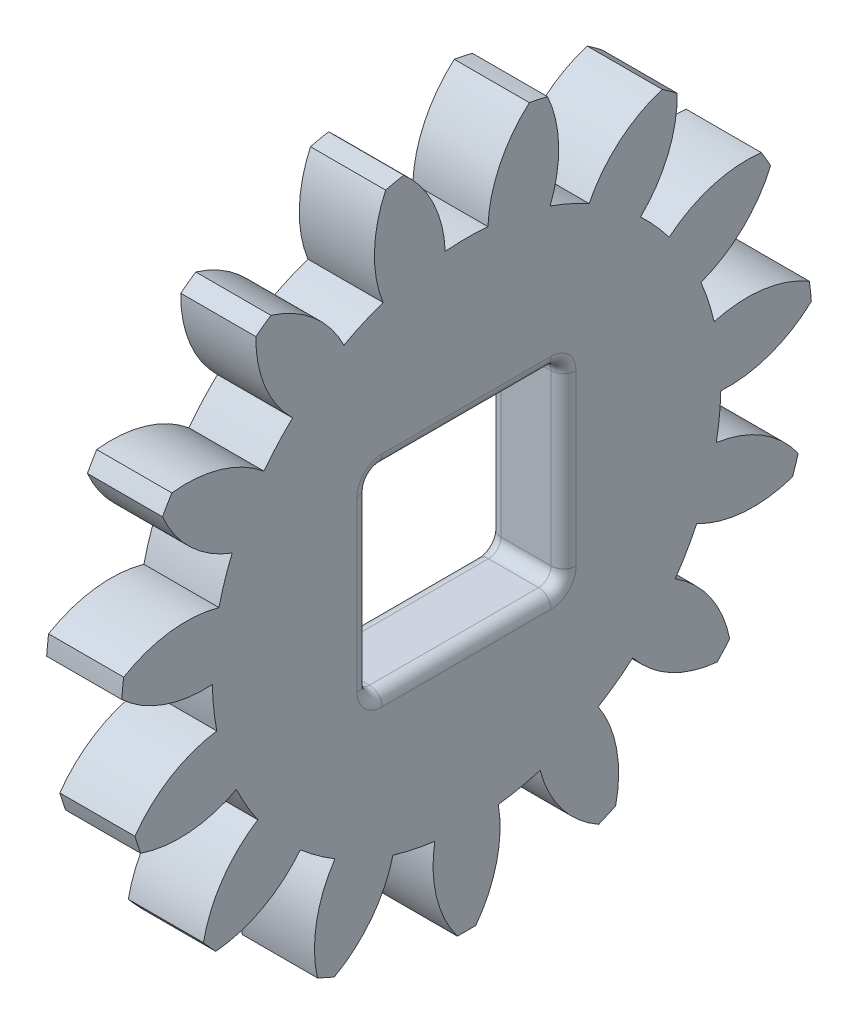
SolidWorks part; units mm, degrees
ref_plane "Plane1" through (0, 0, 0) normal (0, 0, 1) x (1, 0, 0)
ref_plane "Plane2" through (0, 0, 0) normal (0, 1, 0) x (1, 0, 0)
ref_plane "Plane3" through (0, 0, 0) normal (1, 0, 0) x (0, 0, -1)
sketch "HoldingSke" plane through (0, 0, 0) normal (0, 1, 0) x (1, 0, 0)
  line L0 (0, 0) -> (0.1486, -0.0398)
  line L1 (-15, 0) -> (100, 0) construction
  line L2 (0, 0) -> (-2.1039, 2.3779)
  line L3 (0, 0) -> (-11.863, 4.5341)
  line L4 (0, 0) -> (8.3417, 2.2352)
  line L5 (0, 0) -> (-46.8476, -17.4728)
  line L6 (0, 0) -> (-9.9476, -6.7116)
  line L7 (-2.1039, 2.3779) -> (8.6586, 51.2059)
  line L8 (-76.2, 54.61) -> (-73.4, 54.61)
  line L9 (-71.009, 38.7566) -> (-53.1078, 45.2721)
  line L10 (-76.2, 71.12) -> (104.1128, 71.12)
  line L11 (0, 0) -> (-12, 0)
  line L12 (-76.2, 101.6) -> (-75.981, 101.6)
  line L13 (24.9733, 27.94) -> (52.9518, 28.4284)
  line L14 (24.9733, 27.94) -> (24.9743, 27.94)
  line L15 (24.9733, 27.94) -> (100.4006, 29.5858)
  line L16 (-63.627, -6.5) -> (-12.827, -6.5)
  circle A0 centre (0, 0) radius 10
  circle A1 centre (0, 0) radius 37.5
  circle A2 centre (0, 0) radius 37.5
  circle A3 centre (0, 0) radius 10
  dimension "MHD" = 75
  dimension "Hub_dia" = 75
  dimension "Bore" = 20
  dimension "MBD" = 20
  dimension "Num_teeth" = 15
  dimension "Pitch" = 0.1538
  dimension "Overall_len" = 50
  dimension "Show_teeth" = 15
  dimension "Thickness" = 12
  dimension "OAL" = 50.0001
  dimension "T_dim" = 2.8
  dimension "Ap" = 20
  dimension "H" = 19.05
  dimension "Pitch_radius" = 180.3128
  dimension "Width" = 12
  dimension "Backlash" = 0.219
  dimension "Addendum_fac" = 1
  dimension "Dedendum_fac" = 1.25
  dimension "Clearance_fac" = 0.25
  dimension "Dedendum_add" = 0.001
  dimension "Module" = 6.5
sketch "BasProSke" plane through (0, 0, 0) normal (0, 1, 0) x (1, 0, 0)
  line L0 (-10, 0) -> (60, 0) construction
  line L1 (0, 0) -> (0, 55.25)
  line L2 (0, 0) -> (12, 0)
  line L3 (12, 0) -> (12, 55.25)
  line L4 (12, 55.25) -> (0, 55.25)
  dimension "Thickness" = 12
  dimension "Diameter" = 110.5
revolve "Base-Revolve" add sketch "BasProSke" angle 360 about L0
sketch "TooCutSke" plane through (0, 0, 0) normal (1, 0, 0) x (0, 0, -1)
  line L1 (0, 0) -> (0, 107) construction
  line L2 (0, 0) -> (-5.4787, 48.4412) construction
  line L3 (0, 0) -> (-20.1765, 94.9228) construction
  line L4 (-5.4787, 48.4412) -> (-10.0882, 47.4614) construction
  arc A0 (3.4146, 40.4802) -> (-3.4146, 40.4802) centre (0, 0) ccw
  arc A1 (10.058, 54.3526) -> (-10.058, 54.3526) centre (0, 0) ccw
  circle A2 centre (0, 0) radius 48.75 construction
  circle A3 centre (0, 0) radius 45.81 construction
  arc A4 (-3.4146, 40.4802) -> (-10.058, 54.3526) centre (-22.898, 39.6767) ccw
  arc A5 (10.058, 54.3526) -> (3.4146, 40.4802) centre (22.898, 39.6767) ccw
  dimension "Root_dia" = 81.248
  dimension "Overcut_dia" = 110.5508
  dimension "Pitch_dia" = 97.5
  dimension "Base_dia" = 91.62
  dimension "Flank_rad" = 19.5
  dimension "Half_ang" = 12
  dimension "Half_CT" = 4.7125
extrude "ToothCut" cut sketch "TooCutSke" along normal through all
fillet "Breaks" [suppressed] radius 0.13
fillet "RootFillets" [suppressed] radius 1.626
pattern_circular "TeethCuts" count 15 every 24 about axis through (-10, 0, 0) along (1, 0, 0) of "ToothCut", "RootFillets", "Breaks"
sketch "HubNeaOneSke" plane through (0, 0, 0) normal (-1, 0, 0) x (0, 0, 1)
  circle A0 centre (0, 0) radius 37.5
  dimension "Diameter" = 75
extrude "HubNearOne" [suppressed] add sketch "HubNeaOneSke" along normal blind 38.0001
sketch "HubNeaBotSke" plane through (0, 0, 0) normal (-1, 0, 0) x (0, 0, 1)
  circle A0 centre (0, 0) radius 37.5
  dimension "Diameter" = 75
extrude "HubNearBoth" [suppressed] add sketch "HubNeaBotSke" along normal blind 19
ref_plane "FarPln" through (12, 0, 0) normal (1, 0, 0) x (0, 0, -1)
sketch "HubFarSke" plane through (12, 0, 0) normal (1, 0, 0) x (0, 0, -1)
  circle A0 centre (0, 0) radius 37.5
  dimension "Diameter" = 75
extrude "HubFar" [suppressed] add sketch "HubFarSke" along normal blind 19
sketch "BorSke" plane through (0, 0, 0) normal (1, 0, 0) x (0, 0, -1)
  circle A0 centre (0, 0) radius 10
  dimension "Diameter" = 20
extrude "Bore" cut sketch "BorSke" along normal mid plane 100.0001
sketch "KeySke" plane through (0, 0, 0) normal (1, 0, 0) x (0, 0, -1)
  line L0 (-3, 0) -> (-3, 12.8)
  line L1 (-3, 12.8) -> (3, 12.8)
  line L2 (3, 12.8) -> (3, 0)
  line L3 (0, 0) -> (0, 34) construction
  line L4 (-3, 0) -> (3, 0)
  dimension "Offset" = 12.8
  dimension "Width" = 6
extrude "Keyway" [suppressed] cut sketch "KeySke" along normal mid plane 100.0001
pattern_circular "Keyway2" [suppressed] count 2 every 90 about axis through (-10, 0, 0) along (1, 0, 0)
sketch "Sketch1" plane through (12, 0, 0) normal (1, 0, 0) x (0, 0, -1)
  line L1 (-15.5, -15.5) -> (15.5, -15.5)
  line L2 (-15.5, -15.5) -> (-15.5, 15.5)
  line L3 (-15.5, 15.5) -> (15.5, 15.5)
  line L4 (15.5, -15.5) -> (15.5, 15.5)
  line L5 (-15.5, -15.5) -> (15.5, 15.5) construction
  line L6 (-15.5, 15.5) -> (15.5, -15.5) construction
  point P0 (0, 0)
extrude "Cut-Extrude2" cut sketch "Sketch1" against normal through all
fillet "Fillet1" radius 2 12 edges at (6, 15.5, -15.5) (12, 0, -15.5) (0, 0, -15.5) (6, -15.5, -15.5) (12, -15.5, 0) (0, -15.5, 0) (6, -15.5, 15.5) (0, 0, 15.5) (12, 0, 15.5) (0, 15.5, 0) (12, 15.5, 0) (6, 15.5, 15.5)
equation "' \"Module@HoldingSke\" = 6.35"
equation "' \"Num_teeth@HoldingSke\" = 12"
equation "' \"Ap@HoldingSke\" =  20"
equation "' \"Ap@HoldingSke\" = 20"
equation "' \"Width@HoldingSke\" = 0.5 * 25.4"
equation "' \"Hub_dia@HoldingSke\"= 1 * 25.4"
equation "' \"Hub_dia@HoldingSke\" = 1 * 25.4"
equation "' \"Overall_len@HoldingSke\" = 1.0 * 25.4"
equation "' \"Bore@HoldingSke\" = 0.75 * 25.4"
equation "' \"T_dim@HoldingSke\" = 0.1 * 25.4"
equation "' \"Width@KeySke\" = 0.25 * 25.4"
equation "' \"Show_teeth@HoldingSke\" = 13"
equation "' \"Backlash@HoldingSke\" = 0.009 * 25.4"
equation "' \"Addendum_fac@HoldingSke\" = 1.0"
equation "' \"Dedendum_fac@HoldingSke\" = 1.25"
equation "' \"Dedendum_add@HoldingSke\" = 0.00005 * 25.4"
equation "' \"Clearance_fac@HoldingSke\" = 0.25"
equation "\"Pitch@HoldingSke\" = 1 / \"Module@HoldingSke\""
equation "\"Overcut_dia@TooCutSke\" = (\"Num_teeth@HoldingSke\" + 2 * \"Addendum_fac@HoldingSke\") / \"Pitch@HoldingSke\" + 0.002 * 25.4"
equation "\"Pitch_dia@TooCutSke\" = \"Num_teeth@HoldingSke\" / \"Pitch@HoldingSke\""
equation "\"Base_dia@TooCutSke\" = \"Num_teeth@HoldingSke\" / \"Pitch@HoldingSke\" * cos((\"Ap@HoldingSke\"  * 3.14159265 / 180))"
equation "\"Root_dia@TooCutSke\" = (\"Num_teeth@HoldingSke\" + 2) / \"Pitch@HoldingSke\" - 2 * (\"Addendum_fac@HoldingSke\" + \"Dedendum_fac@HoldingSke\") / \"Pitch@HoldingSke\" - \"Dedendum_add@HoldingSke\" * 2"
equation "\"Half_ang@TooCutSke\" = 180 / \"Num_teeth@HoldingSke\""
equation "\"Half_CT@TooCutSke\" = \"Num_teeth@HoldingSke\" / \"Pitch@HoldingSke\" * sin((3.14159265 / 2 / \"Num_teeth@HoldingSke\")) / 2 - 7 * \"Backlash@HoldingSke\" / 4"
equation "\"Flank_rad@TooCutSke\" = \"Num_teeth@HoldingSke\" / \"Pitch@HoldingSke\" / 5"
equation "\"Radius@RootFillets\" = \"Clearance_fac@HoldingSke\" / \"Pitch@HoldingSke\" + \"Dedendum_add@HoldingSke\""
equation "\"Break_rad@Breaks\" = 0.02 / \"Pitch@HoldingSke\""
equation "\"Thickness@HoldingSke\" = \"Width@HoldingSke\""
equation "\"OAL@HoldingSke\" = \"Thickness@HoldingSke\""
equation "\"MHD@HoldingSke\" = (\"Num_teeth@HoldingSke\" + 2) / \"Pitch@HoldingSke\" - 2 * (\"Addendum_fac@HoldingSke\" + \"Dedendum_fac@HoldingSke\")  / \"Pitch@HoldingSke\" - \"Dedendum_add@HoldingSke\" * 2"
equation "\"MBD@HoldingSke\" = (\"Num_teeth@HoldingSke\" + 2) / \"Pitch@HoldingSke\" - 2 * (\"Addendum_fac@HoldingSke\" + \"Dedendum_fac@HoldingSke\")  / \"Pitch@HoldingSke\" - \"Dedendum_add@HoldingSke\" * 2 - 0.002 * 25.4"
equation "\"MHD@HoldingSke\" = ((sgn( \"MHD@HoldingSke\" - \"Hub_dia@HoldingSke\" )-1)*( \"MHD@HoldingSke\" - \"Hub_dia@HoldingSke\" ))/-2+ \"Hub_dia@HoldingSke\""
equation "\"MBD@HoldingSke\" = ((sgn( \"MBD@HoldingSke\" - \"Bore@HoldingSke\" )-1)*( \"MBD@HoldingSke\" - \"Bore@HoldingSke\" ))/-2+ \"Bore@HoldingSke\""
equation "\"OAL@HoldingSke\" = ((sgn( \"OAL@HoldingSke\" - \"Overall_len@HoldingSke\" )+1)*( \"OAL@HoldingSke\" - \"Overall_len@HoldingSke\" ))/2 + \"Overall_len@HoldingSke\" + 0.000002 * 25.4"
equation "\"Num_teeth@TeethCuts\" = int( \"Show_teeth@HoldingSke\" ) + 1"
equation "\"Num_teeth@TeethCuts\" = ((sgn( \"Num_teeth@TeethCuts\" - \"Num_teeth@HoldingSke\" )-1)*( \"Num_teeth@TeethCuts\" - \"Num_teeth@HoldingSke\" ))/-2+ \"Num_teeth@HoldingSke\""
equation "\"Num_teeth@TeethCuts\" = ((sgn( \"Num_teeth@TeethCuts\" - 2.0)+1)*( \"Num_teeth@TeethCuts\" - 2.0))/2 +2.0"
equation "\"Angle@TeethCuts\" = 360.0 / \"Num_teeth@HoldingSke\""
equation "\"Diameter@BasProSke\" = (\"Num_teeth@HoldingSke\" + 2 * \"Addendum_fac@HoldingSke\") / \"Pitch@HoldingSke\""
equation "\"Thickness@BasProSke\"  = \"Thickness@HoldingSke\""
equation "' \"Fillet_rad@BasProSke\" =  \"Thickness@HoldingSke\" * 0.05"
equation "' \"Fillet_rad@BasProSke\" = \"Thickness@HoldingSke\" * 0.05"
equation "\"MHD@HoldingSke\" = ((sgn( \"MHD@HoldingSke\" - \"Root_dia@TooCutSke\" )-1)*( \"MHD@HoldingSke\" - \"Root_dia@TooCutSke\" ))/-2+ \"Root_dia@TooCutSke\""
equation "\"Diameter@HubNeaOneSke\" = \"MHD@HoldingSke\""
equation "\"Length@HubNearOne\" = \"OAL@HoldingSke\" - \"Thickness@BasProSke\""
equation "\"Diameter@HubNeaBotSke\" = \"MHD@HoldingSke\""
equation "\"Length@HubNearBoth\" = ( \"OAL@HoldingSke\" - \"Thickness@BasProSke\" ) / 2.0"
equation "\"Thickness@FarPln\" = \"Thickness@BasProSke\""
equation "\"Diameter@HubFarSke\" = \"MHD@HoldingSke\""
equation "\"Length@HubFar\" = ( \"OAL@HoldingSke\" - \"Thickness@BasProSke\" ) / 2.0"
equation "\"Diameter@BorSke\" = \"MBD@HoldingSke\""
equation "\"D1@Bore\" = \"OAL@HoldingSke\" * 2.0"
equation "\"D1@Keyway\" = \"OAL@HoldingSke\" * 2.0"
equation "\"Offset@KeySke\" = \"T_dim@HoldingSke\" + \"MBD@HoldingSke\" / 2.0"
